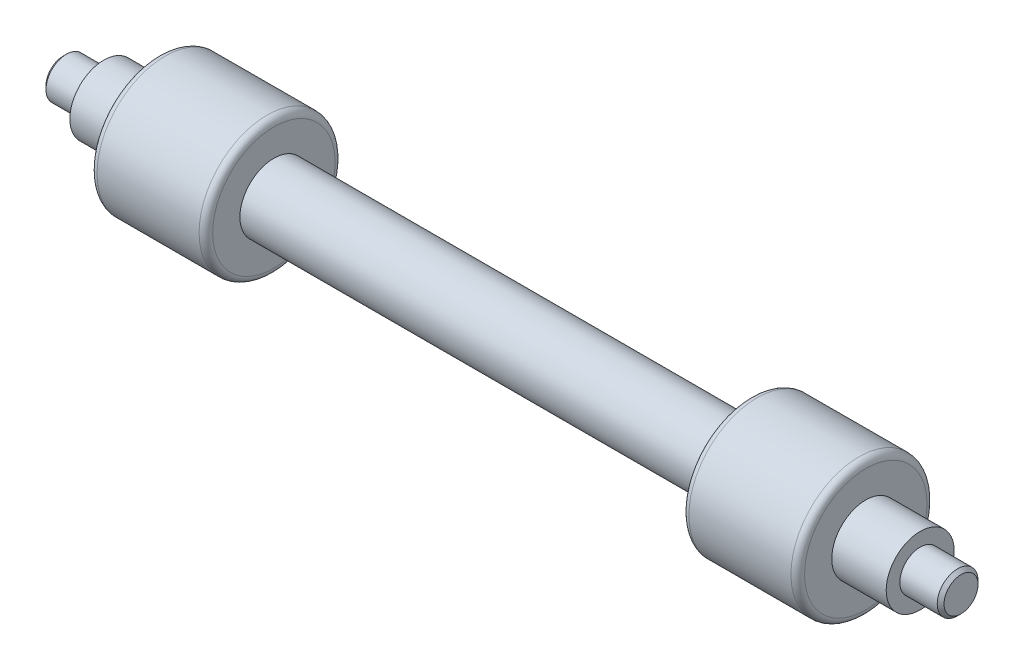
SolidWorks part; units mm, degrees
ref_plane "Front Plane" through (0, 0, 0) normal (0, 0, 1) x (1, 0, 0)
ref_plane "Top Plane" through (0, 0, 0) normal (0, 1, 0) x (1, 0, 0)
ref_plane "Right Plane" through (0, 0, 0) normal (1, 0, 0) x (0, 0, -1)
sketch "Sketch1" plane through (0, 0, 0) normal (0, 0, 1) x (1, 0, 0)
  line L0 (-35.809, 0) -> (45.5053, 0) construction
  line L1 (33, 0) -> (33, 1.5)
  line L2 (33, 1.5) -> (30, 1.5)
  line L3 (30, 1.5) -> (30, 2.5)
  line L4 (30, 2.5) -> (-30, 2.5)
  line L5 (-30, 2.5) -> (-30, 1.5)
  line L6 (-30, 1.5) -> (-33, 1.5)
  line L7 (-33, 1.5) -> (-33, 0)
  line L8 (-33, 0) -> (33, 0)
  point P5 (0, 0)
  dimension "D1" = 1.5
  dimension "D2" = 3
  dimension "D3" = 60
  dimension "D4" = 2.5
revolve "Revolve1" add sketch "Sketch1" angle 360 about L0
cosmetic thread "Cosmetic Thread1" parameters "D2"=2.439
cosmetic thread "Cosmetic Thread2" parameters "D2"=2.439
sketch "Sketch2" plane through (0, 0, 0) normal (0, 0, 1) x (1, 0, 0)
  line L0 (-26, 2.5) -> (-26, 5)
  line L1 (30, 2.5) -> (-30, 2.5) construction
  line L2 (-26, 5) -> (-17.5, 5)
  line L3 (-17.5, 5) -> (-17.5, 2.5)
  line L4 (-17.5, 2.5) -> (-26, 2.5)
  line L5 (17.5, 2.5) -> (17.5, 5)
  line L6 (17.5, 5) -> (26, 5)
  line L7 (26, 5) -> (26, 2.5)
  line L8 (26, 2.5) -> (17.5, 2.5)
  line L9 (17.5, 2.5) -> (-17.5, 2.5) construction
  point P8 (0, 2.5)
  dimension "D1" = 5
  dimension "D2" = 8.5
  dimension "D3" = 4
revolve "Revolve2" add sketch "Sketch2" angle 360 about L0
fillet "Fillet1" radius 0.5 2 edges at (-17.5, 0, 5) (-26, 0, 5)
fillet "Fillet2" radius 0.5 2 edges at (17.5, 0, 5) (26, 0, 5)
chamfer "Chamfer1" distance 0.25 angle 45 2 edges at (33, 0, 1.5) (-33, 0, 1.5)
